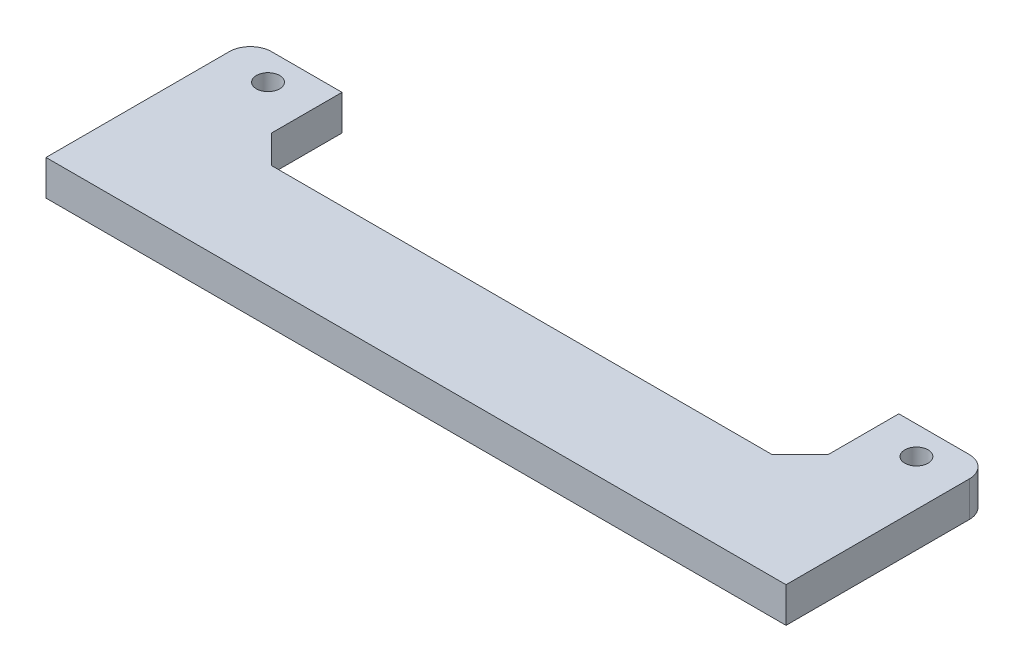
SolidWorks part; units mm, degrees
ref_plane "Front Plane" through (0, 0, 0) normal (0, 0, 1) x (1, 0, 0)
ref_plane "Top Plane" through (0, 0, 0) normal (0, 1, 0) x (1, 0, 0)
ref_plane "Right Plane" through (0, 0, 0) normal (1, 0, 0) x (0, 0, -1)
sketch "Sketch1" plane through (0, 0, 0) normal (0, 1, 0) x (1, 0, 0)
  line L0 (0, 0) -> (-52.5, 0)
  line L1 (-52.5, 0) -> (-52.5, 29)
  line L2 (-52.5, 29) -> (-39.5, 29)
  line L3 (-39.5, 29) -> (-39.5, 15)
  line L4 (-39.5, 15) -> (0, 15)
  line L5 (0, 15) -> (0, 0)
  line L6 (0, 0) -> (0, 48.6971) construction
  line L7 (-46, 0) -> (-46, 29) construction
  circle A0 centre (-46, 25) radius 1.65
  point P4 (0, 0)
  point P12 (0, 0)
  point P17 (-46, 29)
  dimension "D1" = 3.3
  dimension "D2" = 10
  dimension "D3" = 15
  dimension "D4" = 4
  dimension "D5" = 92
  dimension "D6" = 13
extrude "Boss-Extrude1" add sketch "Sketch1" along normal blind 5
mirror "Mirror1" about plane through (0, 0, 0) normal (1, 0, 0) of "Boss-Extrude1"
chamfer "Chamfer1" distance 4 angle 45 2 edges at (39.5, 2.5, -15) (-39.5, 2.5, -15)
fillet "Fillet1" radius 3 2 edges at (52.5, 2.5, -29) (-52.5, 2.5, -29)
